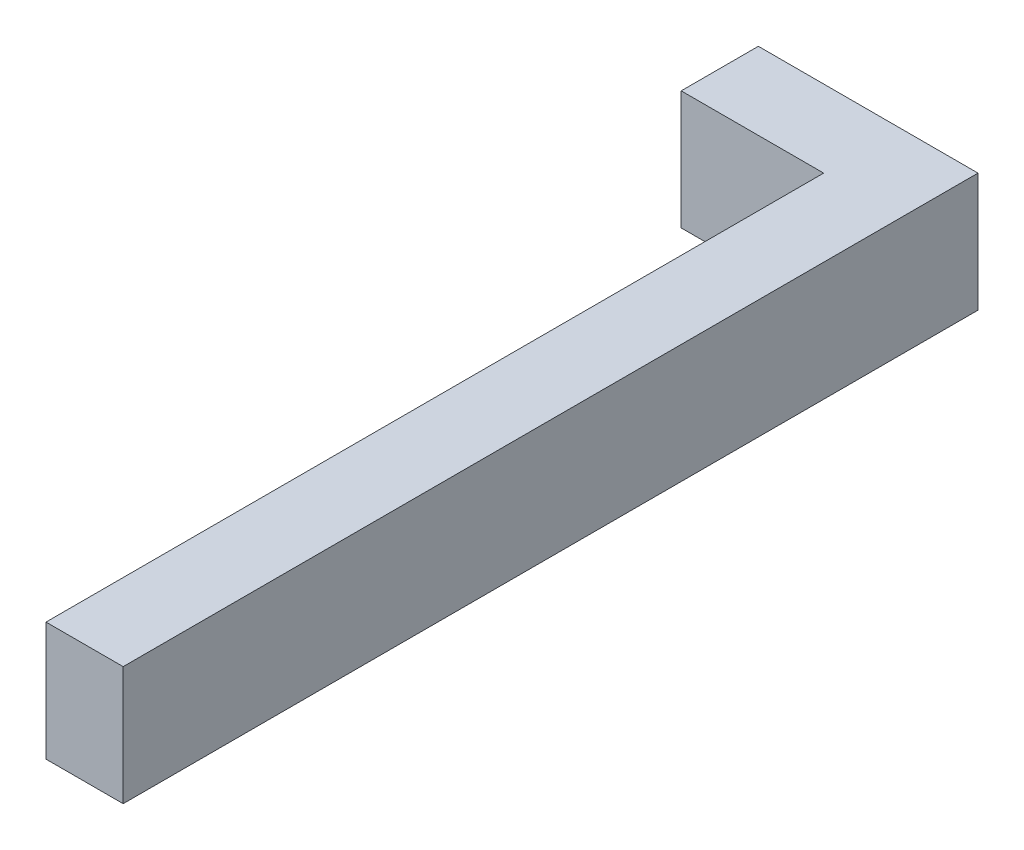
SolidWorks part; units mm, degrees
ref_plane "Front Plane" through (0, 0, 0) normal (0, 0, 1) x (1, 0, 0)
ref_plane "Top Plane" through (0, 0, 0) normal (0, 1, 0) x (1, 0, 0)
ref_plane "Right Plane" through (0, 0, 0) normal (1, 0, 0) x (0, 0, -1)
sketch "Sketch1" plane through (0, 0, 0) normal (0, 1, 0) x (1, 0, 0)
  line L1 (0, 0) -> (152.4, 0)
  line L2 (0, 0) -> (0, 82.55)
  line L3 (0, 82.55) -> (234.95, 82.55)
  line L4 (234.95, 0) -> (234.95, 82.55)
  line L6 (234.95, 0) -> (234.95, -831.85)
  line L7 (234.95, -831.85) -> (152.4, -831.85)
  line L8 (152.4, 0) -> (152.4, -831.85)
  point P8 (234.95, -831.3384)
  point P9 (0, 0)
  point P10 (234.95, -166.475)
  point P11 (234.95, 0)
  dimension "D1" = 152.4
  dimension "D2" = 82.55
  dimension "D3" = 914.4
extrude "Boss-Extrude1" add sketch "Sketch1" along normal blind 127
